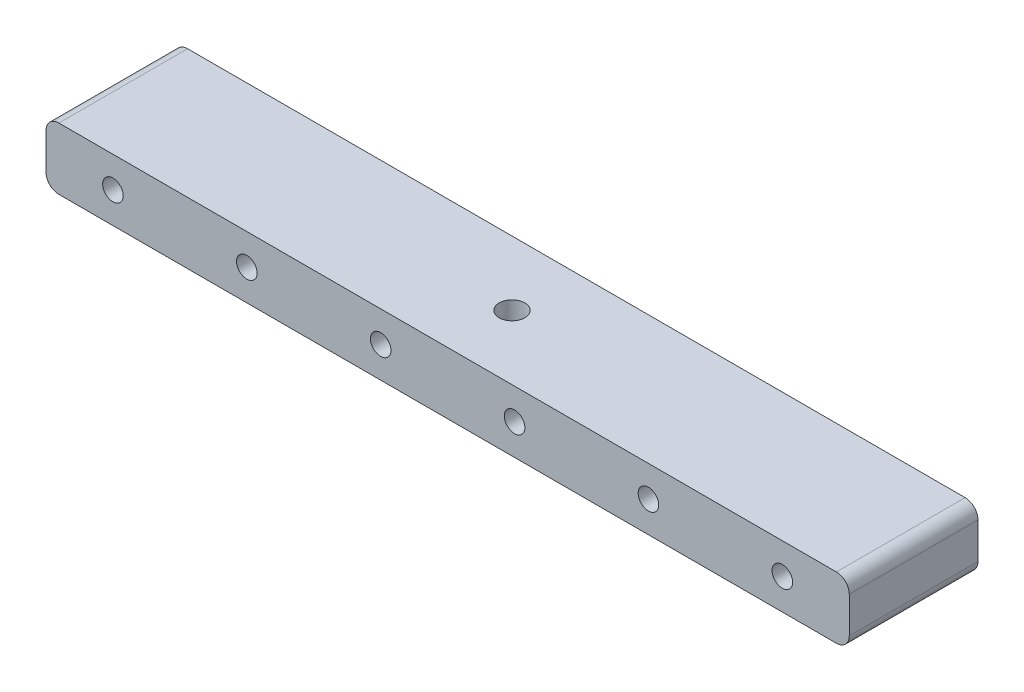
SolidWorks part; units mm, degrees
material "Alumina"
ref_plane "Front Plane" through (0, 0, 0) normal (0, 0, 1) x (1, 0, 0)
ref_plane "Top Plane" through (0, 0, 0) normal (0, 1, 0) x (1, 0, 0)
ref_plane "Right Plane" through (0, 0, 0) normal (1, 0, 0) x (0, 0, -1)
sketch "Sketch1" plane through (0, 0, 0) normal (0, 1, 0) x (1, 0, 0)
  line L0 (-78, -3) -> (78, -3) construction
  line L1 (-78, 12.5) -> (78, 12.5)
  line L2 (-78, 12.5) -> (-78, -12.5)
  line L3 (-78, -12.5) -> (78, -12.5)
  line L4 (78, 12.5) -> (78, -12.5)
  line L5 (-78, 12.5) -> (78, -12.5) construction
  line L6 (-78, -12.5) -> (78, 12.5) construction
  line L7 (0, 0) -> (0, -50000) construction
  circle A0 centre (0, 0) radius 2.5
  point P0 (0, 0)
  dimension "D4" = 5
  dimension "D1" = 25
  dimension "D2" = 156
  dimension "D3" = 9.5
extrude "Boss-Extrude1" add sketch "Sketch1" along normal mid plane 12
cosmetic thread "Cosmetic Thread13" parameters "D2"=6
fillet "Fillet1" radius 2.5 4 edges at (-78, -6, 0) (-78, 6, 0) (78, -6, 0) (78, 6, 0)
sketch "Sketch2" plane through (0, 0, 12.5) normal (0, 0, 1) x (1, 0, 0)
  line L0 (0, 0) -> (-50000, 0) construction
  circle A0 centre (-65, 0) radius 2
  dimension "D1" = 4
  dimension "D2" = 65
extrude "Cut-Extrude1" cut sketch "Sketch2" against normal blind 10
cosmetic thread "Cosmetic Thread1" parameters "D2"=5
pattern_linear "LPattern1" count 6 spacing 26 along (1, 0, 0) of "Cut-Extrude1"
cosmetic thread "Cosmetic Thread2" parameters "D2"=5
cosmetic thread "Cosmetic Thread3" parameters "D2"=5
cosmetic thread "Cosmetic Thread4" parameters "D2"=5
cosmetic thread "Cosmetic Thread5" parameters "D2"=5
cosmetic thread "Cosmetic Thread6" parameters "D2"=5
mirror "Mirror1" about plane through (0, 0, 0) normal (0, 0, 1) of "LPattern1", "Cut-Extrude1"
cosmetic thread "Cosmetic Thread7" parameters "D2"=5
cosmetic thread "Cosmetic Thread8" parameters "D2"=5
cosmetic thread "Cosmetic Thread9" parameters "D2"=5
cosmetic thread "Cosmetic Thread10" parameters "D2"=5
cosmetic thread "Cosmetic Thread11" parameters "D2"=5
cosmetic thread "Cosmetic Thread12" parameters "D2"=5
